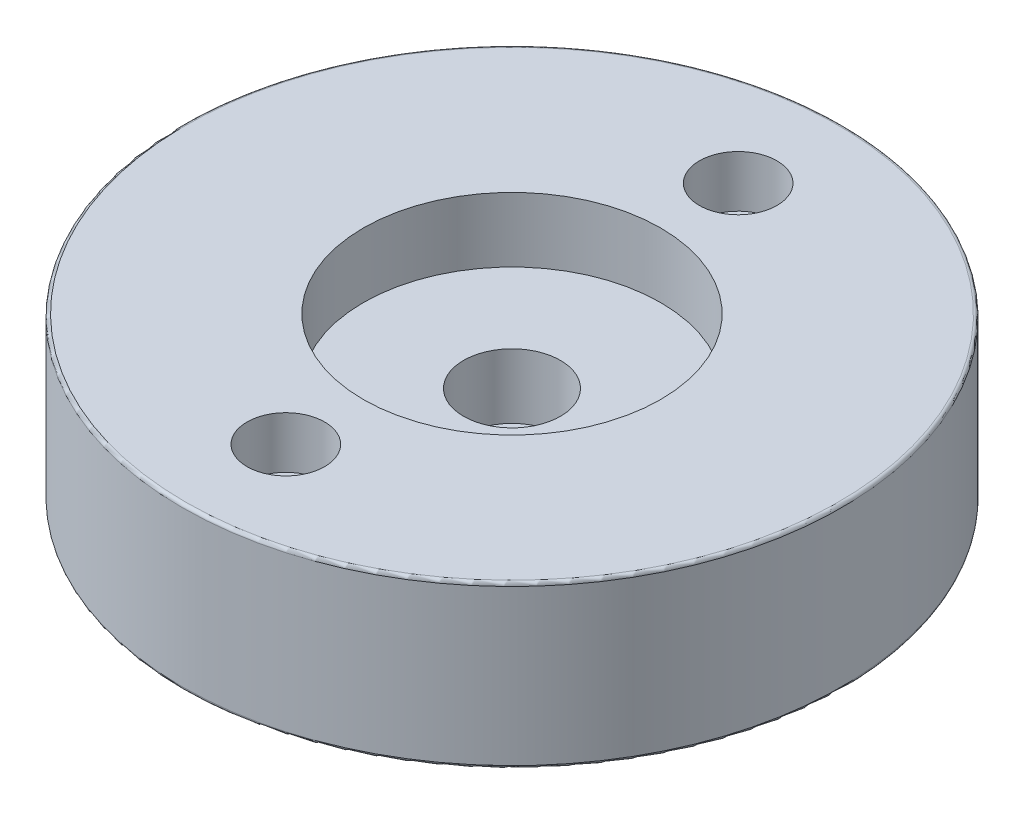
SolidWorks part; units mm, degrees
ref_plane "Front" through (0, 0, 0) normal (0, 0, 1) x (1, 0, 0)
ref_plane "Top" through (0, 0, 0) normal (0, 1, 0) x (1, 0, 0)
ref_plane "Right" through (0, 0, 0) normal (1, 0, 0) x (0, 0, -1)
sketch "Sketch2" plane through (0, 0, 0) normal (0, 1, 0) x (1, 0, 0)
  circle A0 centre (0, 0) radius 64.77
  dimension "D1" = 129.54
extrude "Boss-Extrude1" add sketch "Sketch2" along normal blind 31.75
fillet "Fillet1" radius 0.635 2 edges at (0, 0, 64.77) (0, 31.75, 64.77)
sketch "Sketch3" plane through (0, 31.75, 0) normal (0, 1, 0) x (1, 0, 0)
  circle A0 centre (0, 0) radius 29.21
  dimension "D1" = 58.42
extrude "Cut-Extrude1" cut sketch "Sketch3" against normal blind 12.7
sketch "Sketch4" plane through (0, 19.05, 0) normal (0, 1, 0) x (1, 0, 0)
  circle A0 centre (0, 0) radius 9.525
  dimension "D1" = 19.05
extrude "Cut-Extrude2" cut sketch "Sketch4" against normal blind 12.7
sketch "Sketch5" plane through (0, 31.75, 0) normal (0, 1, 0) x (1, 0, 0)
  line L0 (-64.5358, 0) -> (91.1164, 0) construction
  circle A0 centre (0, -44.45) radius 7.62
  circle A1 centre (0, 44.45) radius 7.62
  dimension "D1" = 15.24
  dimension "D2" = 44.45
extrude "Cut-Extrude3" cut sketch "Sketch5" against normal blind 10.16
